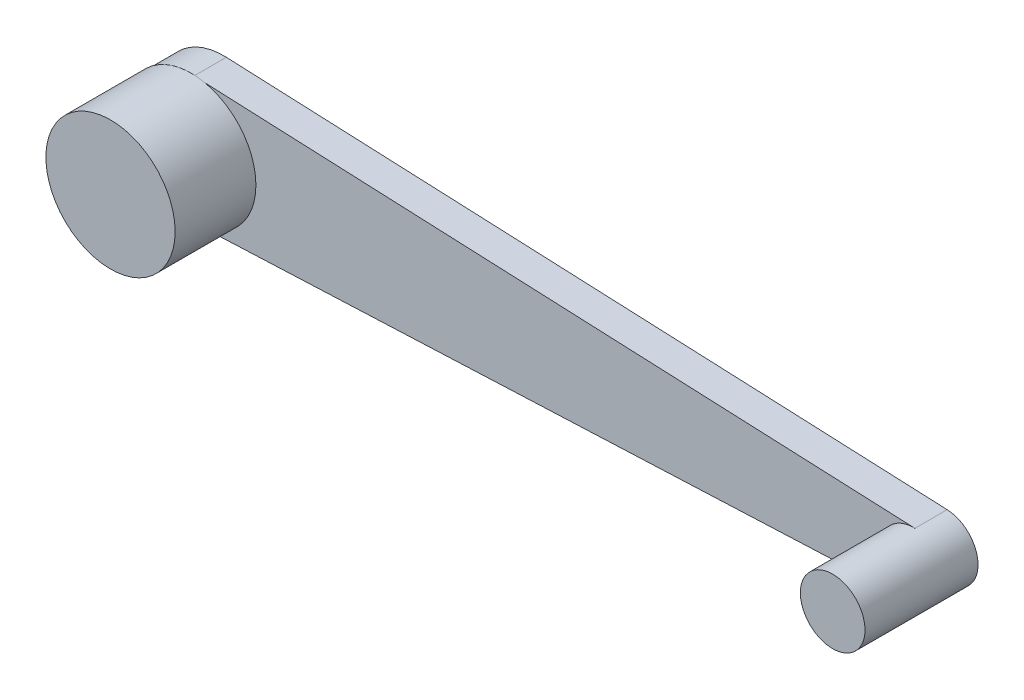
SolidWorks part; units mm, degrees
ref_plane "Front Plane" through (0, 0, 0) normal (0, 0, 1) x (1, 0, 0)
ref_plane "Top Plane" through (0, 0, 0) normal (0, 1, 0) x (1, 0, 0)
ref_plane "Right Plane" through (0, 0, 0) normal (1, 0, 0) x (0, 0, -1)
sketch "Sketch2" plane through (0, 0, 0) normal (0, 0, 1) x (1, 0, 0)
  line L0 (0, 0) -> (44.7, 0) construction
  line L2 (0.1715, 3.9397) -> (44.787, 1.9981)
  line L4 (0.1715, -3.9397) -> (44.787, -1.9981)
  circle A2 centre (0, 0) radius 3.9435 construction
  circle A3 centre (44.7, 0) radius 2 construction
  arc A4 (0.1715, 3.9397) -> (0.1715, -3.9397) centre (0, 0) ccw
  arc A5 (44.787, 1.9981) -> (44.787, -1.9981) centre (44.7, 0) cw
  point P11 (0, 0)
extrude "Boss-Extrude1" add sketch "Sketch2" along normal blind 2
sketch "Sketch3" plane through (0, 0, 2) normal (0, 0, 1) x (1, 0, 0)
  circle A0 centre (0, 0) radius 4
  circle A1 centre (44.7, 0) radius 2
extrude "Boss-Extrude2" add sketch "Sketch3" along normal blind 5
